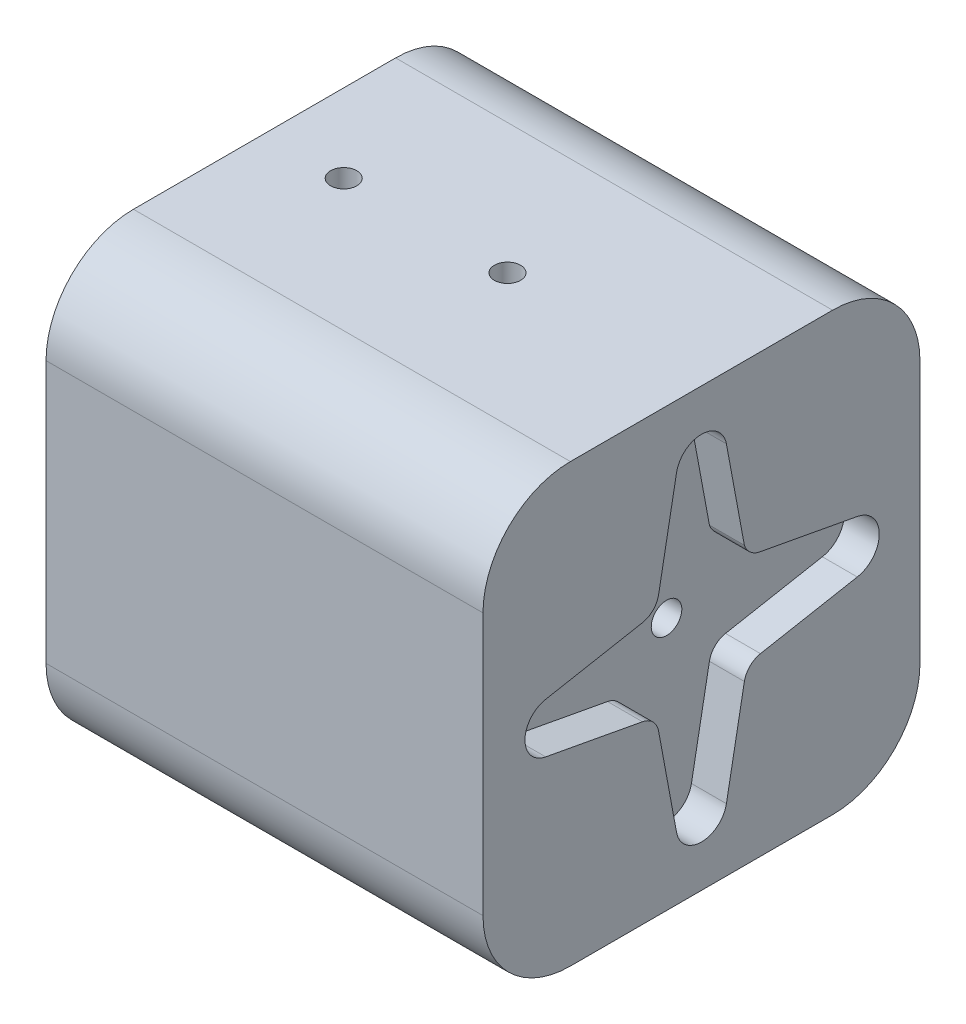
SolidWorks part; units mm, degrees
ref_plane "Plan de face" through (0, 0, 0) normal (0, 0, 1) x (1, 0, 0)
ref_plane "Plan de dessus" through (0, 0, 0) normal (0, 1, 0) x (1, 0, 0)
ref_plane "Plan de droite" through (0, 0, 0) normal (1, 0, 0) x (0, 0, -1)
sketch "Esquisse1" plane through (0, 0, 0) normal (0, 0, 1) x (1, 0, 0)
  line L1 (0, 0) -> (50, 0)
  line L2 (0, 0) -> (0, 50)
  line L3 (0, 50) -> (50, 50)
  line L4 (50, 0) -> (50, 50)
  dimension "D1" = 50
  dimension "D2" = 50
extrude "Boss.-Extru.1" add sketch "Esquisse1" along normal blind 50
sketch "Esquisse2" plane through (0, 0, 0) normal (-1, 0, 0) x (0, 0, 1)
  circle A0 centre (24.9769, 24.8563) radius 6
  dimension "D1" = 12
extrude "Enlèv. mat.-Extru.1" cut sketch "Esquisse2" against normal blind 40
fillet "Congé1" radius 10 4 edges at (25, 0, 50) (25, 50, 0) (25, 50, 50) (25, 0, 0)
sketch "Esquisse3" plane through (0, 50, 0) normal (0, 1, 0) x (1, 0, 0)
  circle A0 centre (8.9582, -24.8946) radius 1.5
  circle A1 centre (27.6954, -24.8946) radius 1.5
  point P4 (27.6954, -24.8946)
  dimension "D1" = 3
extrude "Enlèv. mat.-Extru.2" cut sketch "Esquisse3" against normal blind 21
sketch "Esquisse4" plane through (50, 0, 0) normal (1, 0, 0) x (0, 0, -1)
  line L0 (-14.6472, 30.3429) -> (-14.6472, 73.4856) construction
  line L1 (-7.1447, 28.1358) -> (-18.2242, 30.1928)
  line L2 (-20.0917, 31.7498) -> (-22.1487, 42.8294)
  line L3 (-27.8512, 42.8294) -> (-29.9083, 31.7498)
  line L4 (-31.7498, 29.9083) -> (-42.8293, 27.8513)
  line L5 (-42.8293, 22.1488) -> (-31.7498, 20.0917)
  line L6 (-29.9083, 18.2502) -> (-27.8512, 7.1707)
  line L7 (-22.1487, 7.1707) -> (-20.0917, 18.2502)
  line L8 (-18.2502, 20.0917) -> (-7.1706, 22.1488)
  line L12 (0, 10) -> (0, 40) construction
  line L14 (-40, 50) -> (-10, 50) construction
  arc A0 (-7.1706, 22.1488) -> (-7.1447, 28.1358) centre (-7.7, 25.1446) ccw
  arc A1 (-20.0917, 31.7498) -> (-18.2242, 30.1928) centre (-17.9076, 32.471) ccw
  arc A2 (-22.1487, 42.8294) -> (-27.8512, 42.8294) centre (-25, 42.3) ccw
  arc A3 (-31.7498, 29.9083) -> (-29.9083, 31.7498) centre (-32.1696, 32.1697) ccw
  arc A4 (-42.8293, 27.8513) -> (-42.8293, 22.1488) centre (-42.2999, 25) ccw
  arc A5 (-29.9083, 18.2502) -> (-31.7498, 20.0917) centre (-32.1696, 17.8304) ccw
  arc A6 (-27.8512, 7.1707) -> (-22.1487, 7.1707) centre (-25, 7.7001) ccw
  arc A7 (-18.2502, 20.0917) -> (-20.0917, 18.2502) centre (-17.8303, 17.8304) ccw
  dimension "D2" = 7.7
  dimension "D1" = 7.7
extrude "Enlèv. mat.-Extru.3" cut sketch "Esquisse4" against normal blind 4
sketch "Esquisse5" plane through (46, 0, 0) normal (1, 0, 0) x (0, 0, -1)
  line L0 (-30.5433, 30.5434) -> (-19.4566, 19.4567) construction
  line L1 (-30.5433, 19.4567) -> (-19.3805, 30.7044) construction
  circle A0 centre (-25, 25) radius 1.75
  arc A1 (-31.7498, 29.9083) -> (-29.9083, 31.7498) centre (-32.1696, 32.1697) ccw construction
  arc A2 (-18.2502, 20.0917) -> (-20.0917, 18.2502) centre (-17.8303, 17.8304) ccw construction
  arc A3 (-29.9083, 18.2502) -> (-31.7498, 20.0917) centre (-32.1696, 17.8304) ccw construction
  arc A4 (-20.0917, 31.7498) -> (-18.2242, 30.1928) centre (-17.9076, 32.471) ccw construction
  point P18 (-23.9266, 25.1446)
  dimension "D1" = 3.5
extrude "Enlèv. mat.-Extru.4" cut sketch "Esquisse5" against normal blind 90
